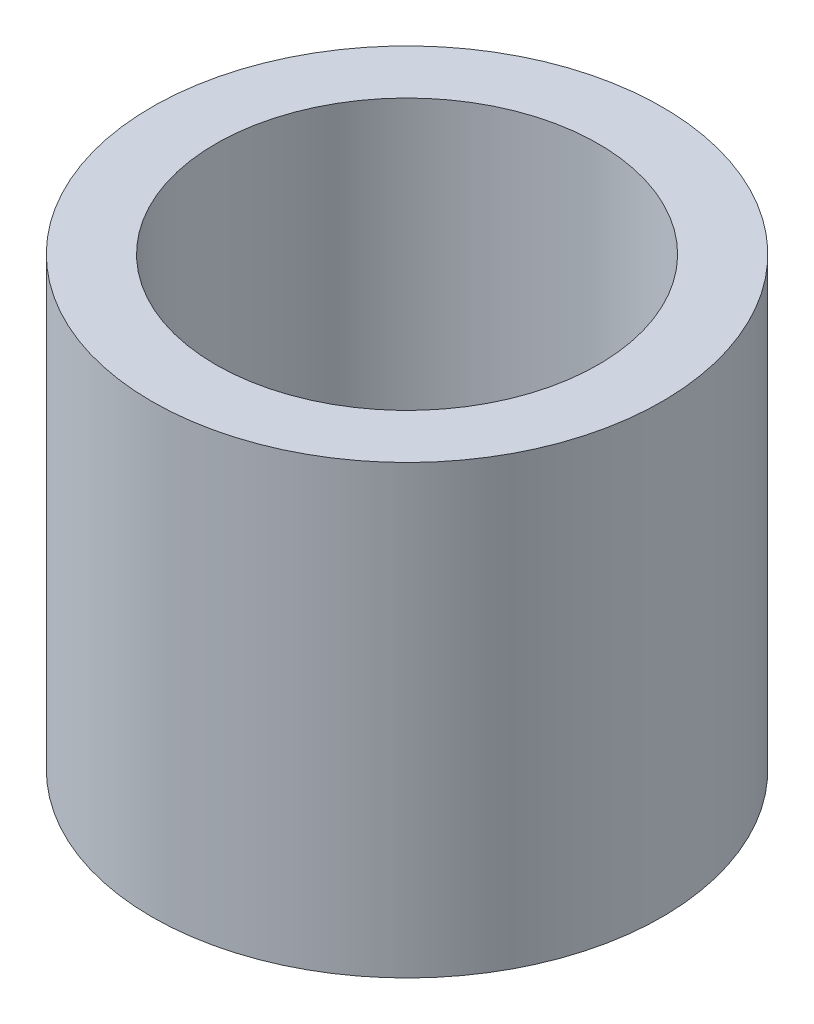
SolidWorks part; units mm, degrees
ref_plane "前视基准面" through (0, 0, 0) normal (0, 0, 1) x (1, 0, 0)
ref_plane "上视基准面" through (0, 0, 0) normal (0, 1, 0) x (1, 0, 0)
ref_plane "右视基准面" through (0, 0, 0) normal (1, 0, 0) x (0, 0, -1)
sketch "草图1" plane through (0, 0, 0) normal (0, 1, 0) x (1, 0, 0)
  circle A0 centre (0, 0) radius 4
  circle A1 centre (0, 0) radius 3
  dimension "D1" = 8
  dimension "D2" = 6
extrude "凸台-拉伸1" add sketch "草图1" along normal blind 7
